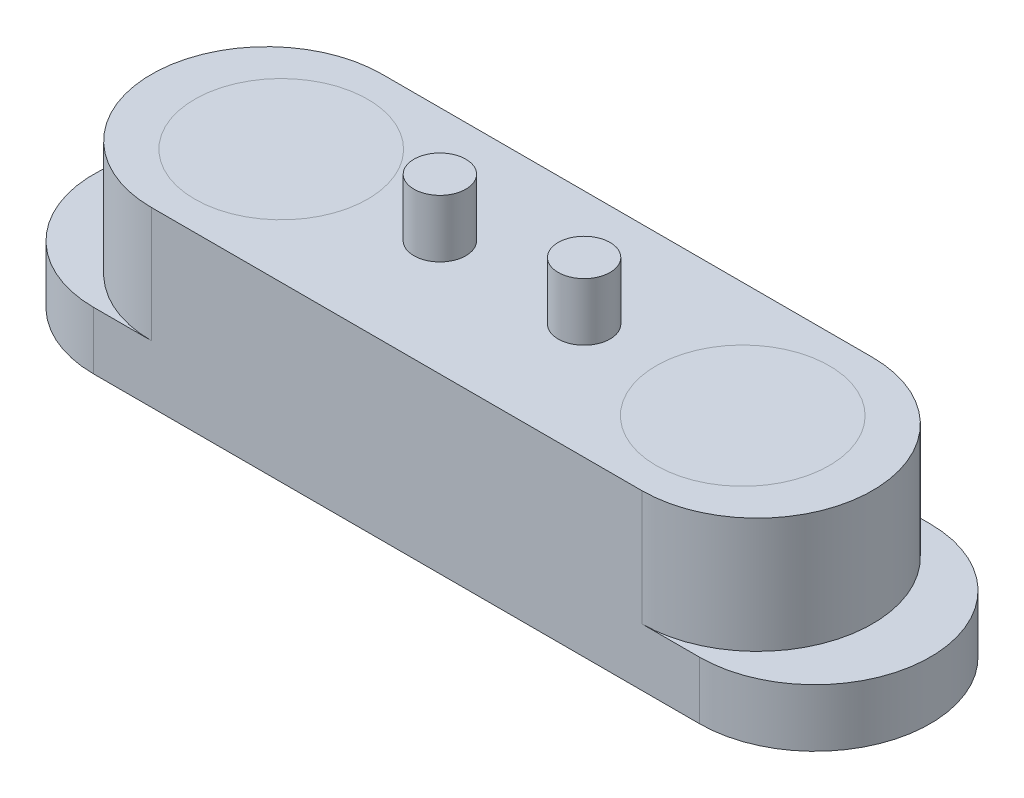
SolidWorks part; units mm, degrees
ref_plane "Front Plane" through (0, 0, 0) normal (0, 0, 1) x (1, 0, 0)
ref_plane "Top Plane" through (0, 0, 0) normal (0, 1, 0) x (1, 0, 0)
ref_plane "Right Plane" through (0, 0, 0) normal (1, 0, 0) x (0, 0, -1)
sketch "Sketch4" plane through (0, 0, 0) normal (0, 1, 0) x (1, 0, 0)
  line L0 (0, 0) -> (10.5, 0) construction
  line L1 (0, 2) -> (10.5, 2)
  line L2 (0, -2) -> (10.5, -2)
  arc A0 (0, 2) -> (0, -2) centre (0, 0) ccw
  arc A1 (10.5, -2) -> (10.5, 2) centre (10.5, 0) ccw
  point P3 (5.25, 0)
  point P8 (-2, 0)
  point P9 (12.5, 0)
  dimension "D1" = 14.5
  dimension "D2" = 4
extrude "Boss-Extrude2" add sketch "Sketch4" along normal blind 1
sketch "Sketch5" plane through (0, 1, 0) normal (0, 1, 0) x (1, 0, 0)
  line L0 (1, 0) -> (9.5, 0) construction
  line L1 (1, 2) -> (9.5, 2)
  line L2 (1, -2) -> (9.5, -2)
  arc A0 (1, 2) -> (1, -2) centre (1, 0) ccw
  arc A1 (9.5, -2) -> (9.5, 2) centre (9.5, 0) ccw
  point P2 (5.25, 0)
  point P7 (-1, 0)
  point P8 (11.5, 0)
  dimension "D1" = 12.5
  dimension "D2" = 4
  dimension "D3" = 1
  dimension "D4" = 0
extrude "Boss-Extrude3" add sketch "Sketch5" along normal blind 2
sketch "Sketch7" plane through (0, 3, 0) normal (0, 1, 0) x (1, 0, 0)
  circle A0 centre (1.25, 0) radius 1.5
  circle A1 centre (9.25, 0) radius 1.5
  circle A2 centre (4, 0) radius 0.45
  circle A3 centre (6.5, 0) radius 0.45
  point P9 (0, 0)
  dimension "D1" = 3
  dimension "D2" = 3
  dimension "D10" = 0.9
  dimension "D11" = 0.9
  dimension "D3" = 1.25
  dimension "D4" = 0
  dimension "D5" = 8
  dimension "D6" = 0
  dimension "D7" = 0
  dimension "D8" = 0
  dimension "D9" = 2.5
  dimension "D12" = 2.75
extrude "Cut-Extrude1" cut sketch "Sketch7" against normal blind 1
sketch "Sketch8" plane through (0, 2, 0) normal (0, 1, 0) x (1, 0, 0)
  circle A0 centre (1.25, 0) radius 1.5
  circle A1 centre (1.25, 0) radius 1.5 construction
  circle A2 centre (9.25, 0) radius 1.5
  circle A3 centre (9.25, 0) radius 1.5 construction
  dimension "D1" = 0
  dimension "D2" = 0
extrude "Boss-Extrude4" add sketch "Sketch8" along normal up to surface (1 mm away) separate body up to face at (1.25, 3, 1.5)
sketch "Sketch9" plane through (0, 2, 0) normal (0, 1, 0) x (1, 0, 0)
  circle A0 centre (4, 0) radius 0.45
  circle A1 centre (6.5, 0) radius 0.45
  circle A2 centre (4, 0) radius 0.45 construction
  circle A3 centre (6.5, 0) radius 0.45 construction
  dimension "D1" = 0
  dimension "D2" = 0
extrude "Boss-Extrude12" add sketch "Sketch9" along normal blind 2
